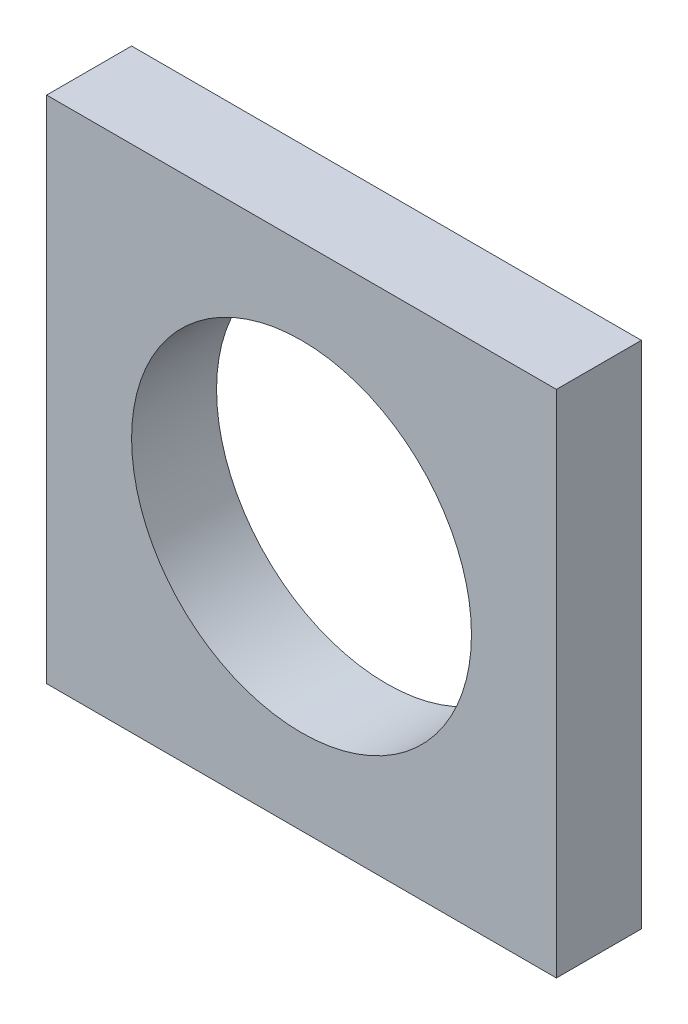
SolidWorks part; units mm, degrees
ref_plane "前视基准面" through (0, 0, 0) normal (0, 0, 1) x (1, 0, 0)
ref_plane "上视基准面" through (0, 0, 0) normal (0, 1, 0) x (1, 0, 0)
ref_plane "右视基准面" through (0, 0, 0) normal (1, 0, 0) x (0, 0, -1)
sketch "草图1" plane through (0, 0, 0) normal (0, 0, 1) x (1, 0, 0)
  line L1 (0, 0) -> (6, 0)
  line L2 (0, 0) -> (0, 6)
  line L3 (0, 6) -> (6, 6)
  line L4 (6, 0) -> (6, 6)
  circle A0 centre (3, 3) radius 2
extrude "凸台-拉伸1" add sketch "草图1" along normal mid plane 1
